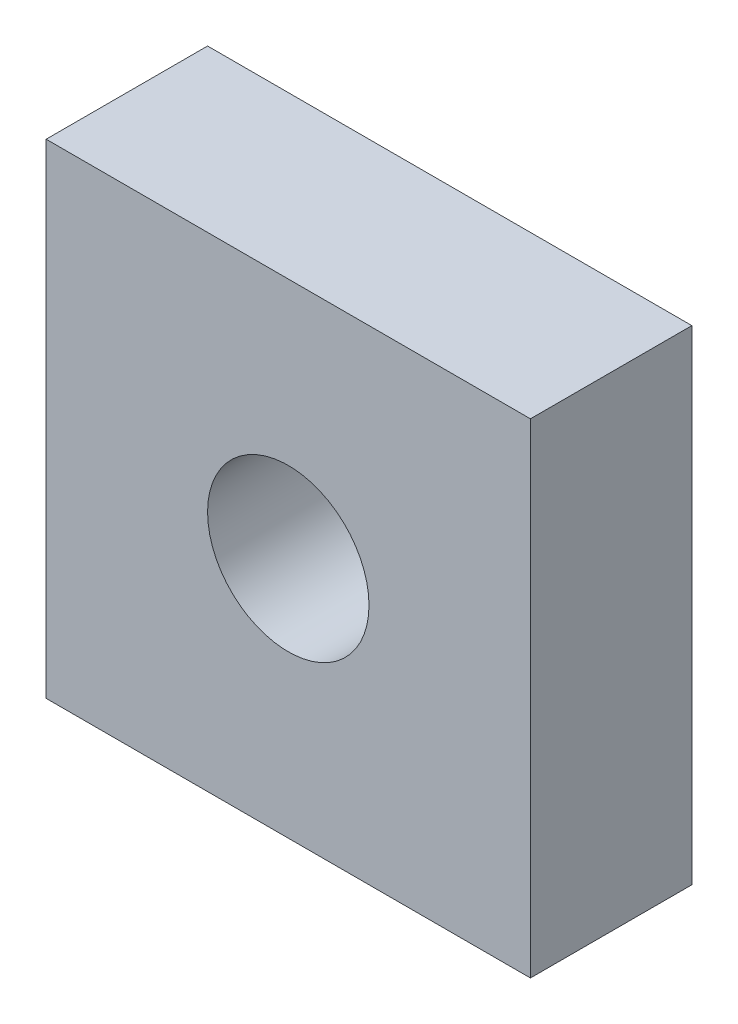
SolidWorks part; units mm, degrees
ref_plane "Plan de face" through (0, 0, 0) normal (0, 0, 1) x (1, 0, 0)
ref_plane "Plan de dessus" through (0, 0, 0) normal (0, 1, 0) x (1, 0, 0)
ref_plane "Plan de droite" through (0, 0, 0) normal (1, 0, 0) x (0, 0, -1)
sketch "Esquisse1" plane through (0, 0, 0) normal (0, 0, 1) x (1, 0, 0)
  line L1 (-15, -15) -> (15, -15)
  line L2 (-15, -15) -> (-15, 15)
  line L3 (-15, 15) -> (15, 15)
  line L4 (15, -15) -> (15, 15)
  line L5 (-15, -15) -> (15, 15) construction
  line L6 (-15, 15) -> (15, -15) construction
  point P0 (0, 0)
  dimension "D1" = 30
  dimension "D2" = 30
extrude "Boss.-Extru.1" add sketch "Esquisse1" along normal blind 10
sketch "Esquisse2" plane through (0, 0, 10) normal (0, 0, 1) x (1, 0, 0)
  circle A0 centre (0, 0) radius 5
  dimension "D1" = 10
extrude "Enlèv. mat.-Extru.1" cut sketch "Esquisse2" against normal blind 10
